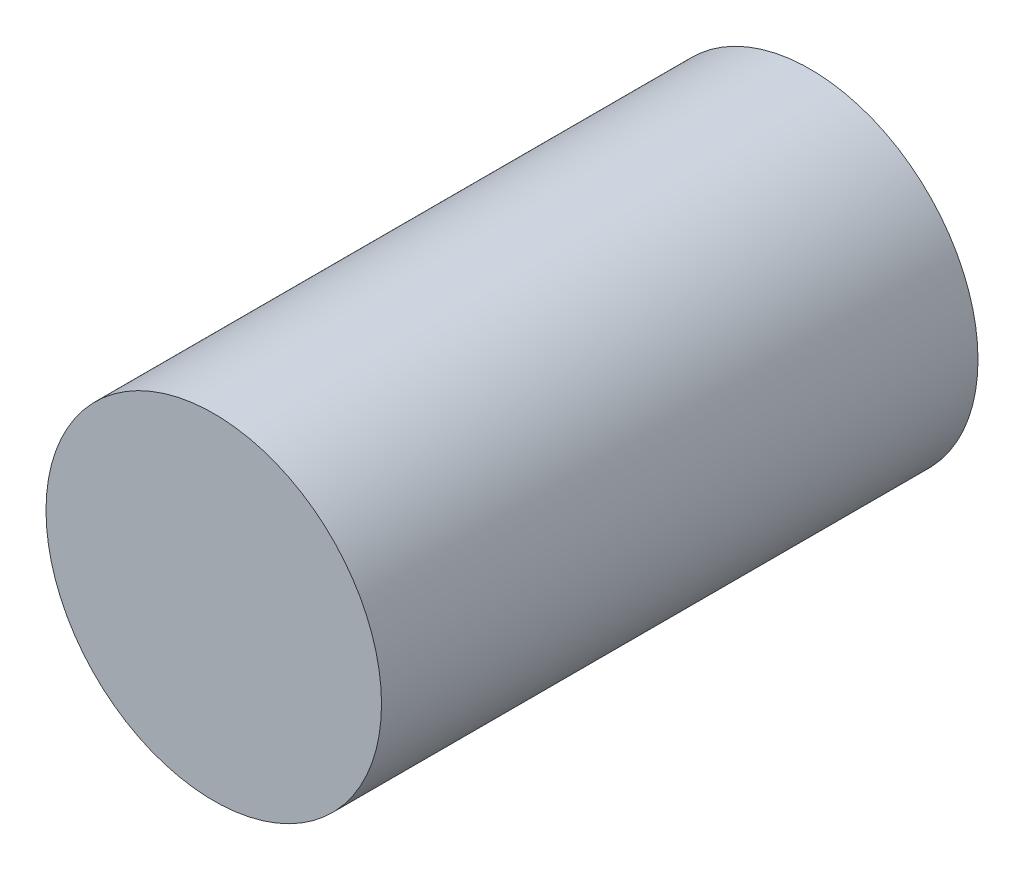
SolidWorks part; units mm, degrees
ref_plane "Front Plane" through (0, 0, 0) normal (0, 0, 1) x (1, 0, 0)
ref_plane "Top Plane" through (0, 0, 0) normal (0, 1, 0) x (1, 0, 0)
ref_plane "Right Plane" through (0, 0, 0) normal (1, 0, 0) x (0, 0, -1)
sketch "Sketch1" plane through (0, 0, 0) normal (0, 0, 1) x (1, 0, 0)
  circle A0 centre (0, 0) radius 14.2875
  dimension "D1" = 28.575
extrude "Boss-Extrude1" add sketch "Sketch1" along normal blind 50.8
